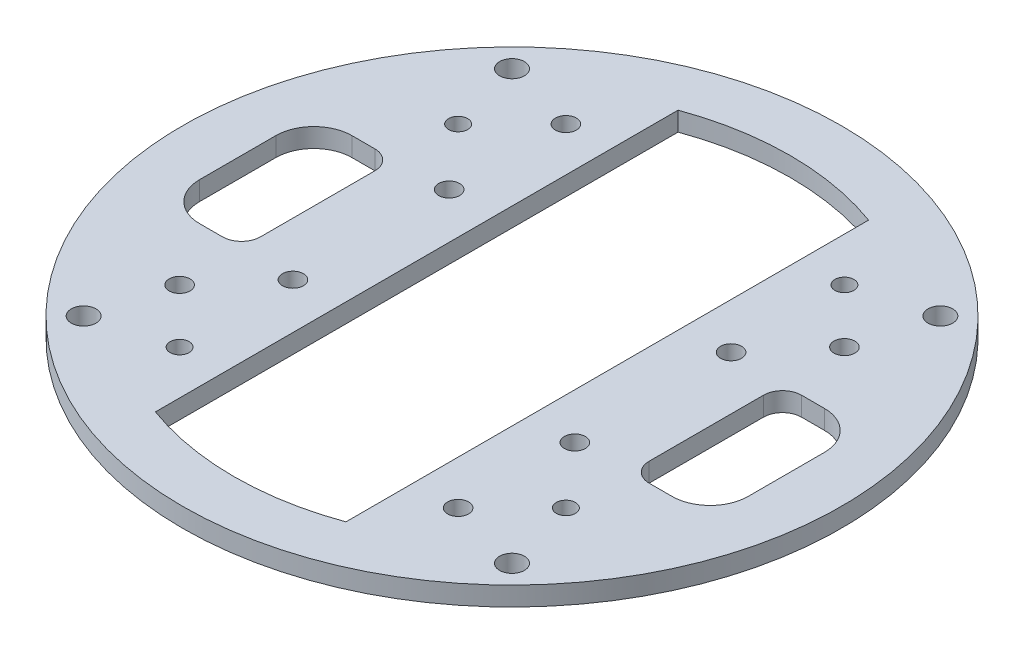
SolidWorks part; units mm, degrees
material "AISI 304"
ref_plane "Front Plane" through (0, 0, 0) normal (0, 0, 1) x (1, 0, 0)
ref_plane "Top Plane" through (0, 0, 0) normal (0, 1, 0) x (1, 0, 0)
ref_plane "Right Plane" through (0, 0, 0) normal (1, 0, 0) x (0, 0, -1)
sketch "Sketch1" plane through (0, 0, 0) normal (0, 1, 0) x (1, 0, 0)
  line L0 (25, 68.5857) -> (25, 20)
  line L1 (56.215, 56.215) -> (0, 0) construction
  line L2 (0, 0) -> (56.215, -56.215) construction
  line L3 (0, 0) -> (0, 79.5) construction
  line L4 (-25, 68.5857) -> (-25, 20)
  line L5 (0, 0) -> (-86.5, 0) construction
  line L6 (-51, 20) -> (-72, 20)
  line L11 (-72, 20) -> (-72, -20)
  line L12 (-72, -20) -> (-51, -20)
  line L13 (-25, -20) -> (-25, -68.5857)
  line L14 (72, -20) -> (51, -20)
  line L15 (72, 20) -> (72, -20)
  line L16 (51, 20) -> (72, 20)
  line L20 (25, -20) -> (25, -68.5857)
  line L23 (25, 20) -> (25, -20)
  line L25 (-51, -20) -> (-51, 20)
  line L27 (51, -20) -> (51, 20)
  line L28 (-25, -20) -> (-25, 20)
  arc A0 (0, -86.5) -> (0, 86.5) centre (0, 0) ccw
  circle A2 centre (0, 0) radius 79.5 construction
  circle A3 centre (56.215, 56.215) radius 3.25
  circle A4 centre (56.215, -56.215) radius 3.25
  circle A5 centre (37, 20.5) radius 2.75
  circle A6 centre (37, -20.5) radius 2.75
  circle A8 centre (-56.215, -56.215) radius 3.25
  circle A9 centre (-37, -20.5) radius 2.75
  circle A10 centre (-37, 20.5) radius 2.75
  circle A11 centre (-56.215, 56.215) radius 3.25
  arc A12 (0, -86.5) -> (0, 86.5) centre (0, 0) cw
  arc A13 (-25, -68.5857) -> (25, -68.5857) centre (0, 0) ccw
  arc A14 (-25, 68.5857) -> (25, 68.5857) centre (0, 0) cw
  point P4 (-72, 0)
  point P31 (-40.7198, 0)
  dimension "D1" = 173
  dimension "D3" = 159
  dimension "D4" = 6.5
  dimension "D5" = 6.5
  dimension "D7" = 5.5
  dimension "D8" = 5.5
  dimension "D12" = 73
  dimension "D14" = 26
  dimension "D17" = 40
  dimension "D2" = 72
  dimension "D6" = 90
  dimension "D9" = 41
  dimension "D10" = 12
  dimension "D11" = 20.5
  dimension "D13" = 25
  dimension "D18" = 26
extrude "Boss-Extrude1" add sketch "Sketch1" along normal blind 5
fillet "Fillet1" radius 10 4 edges at (-72, 2.5, 20) (-72, 2.5, -20) (72, 2.5, 20) (72, 2.5, -20)
fillet "Fillet3" radius 5 4 edges at (-51, 2.5, 20) (-51, 2.5, -20) (51, 2.5, -20) (51, 2.5, 20)
sketch "Sketch3" plane through (0, 5, 0) normal (0, 1, 0) x (1, 0, 0)
  line L0 (-44.1942, -44.1942) -> (0, 0) construction
  line L1 (0, 0) -> (0, -86.5) construction
  line L2 (-36.5538, -50.6959) -> (-50.6959, -36.5538) construction
  circle A0 centre (0, 0) radius 62.5 construction
  circle A5 centre (0, 0) radius 86.5 construction
  circle A10 centre (-50.6959, -36.5538) radius 2.75
  circle A11 centre (-36.5538, -50.6959) radius 2.5
  circle A12 centre (-36.5538, 50.6959) radius 2.75
  circle A13 centre (-50.6959, 36.5538) radius 2.5
  circle A14 centre (50.6959, 36.5538) radius 2.75
  circle A15 centre (36.5538, 50.6959) radius 2.5
  circle A16 centre (36.5538, -50.6959) radius 2.75
  circle A17 centre (50.6959, -36.5538) radius 2.5
  point P8 (-22.0971, -22.0971)
  dimension "D1" = 62.5
  dimension "D2" = 5.5
  dimension "D5" = 20
  dimension "D4" = 5
  dimension "D3" = 45
  dimension "D7" = 4
extrude "Cut-Extrude1" cut sketch "Sketch3" against normal blind 10
